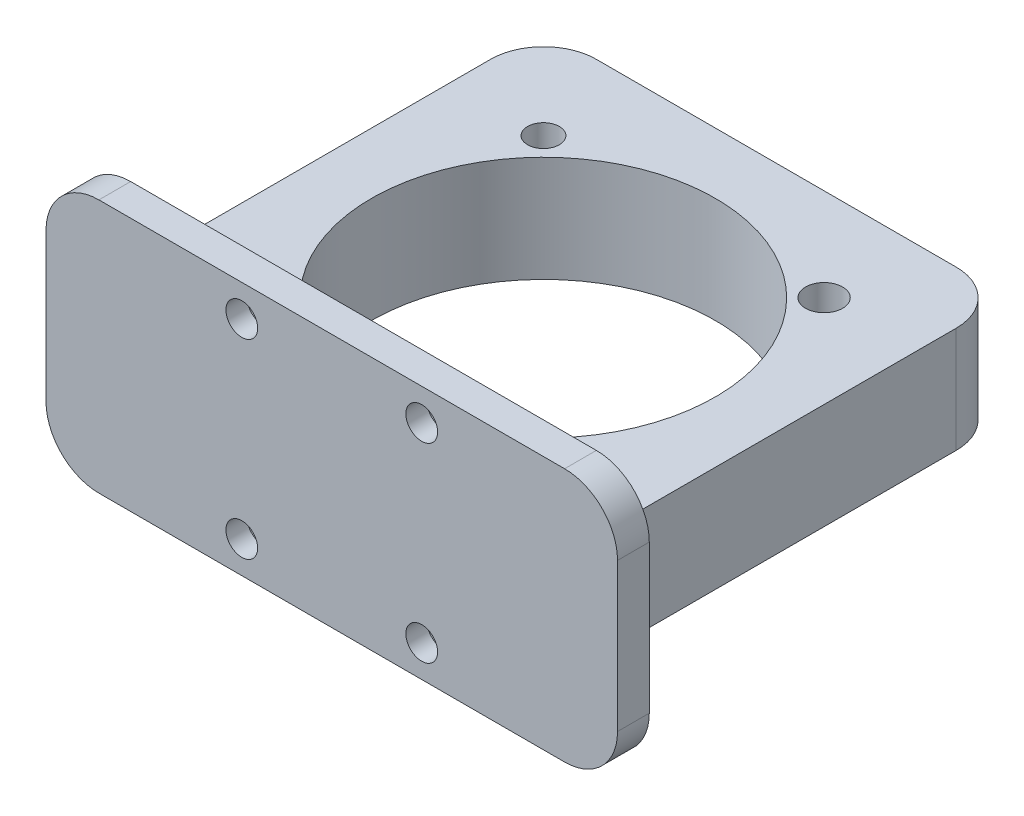
SolidWorks part; units mm, degrees
ref_plane "前视基准面" through (0, 0, 0) normal (0, 0, 1) x (1, 0, 0)
ref_plane "上视基准面" through (0, 0, 0) normal (0, 1, 0) x (1, 0, 0)
ref_plane "右视基准面" through (0, 0, 0) normal (1, 0, 0) x (0, 0, -1)
other "Configuration Table"
sketch "草图1" plane through (0, 0, 0) normal (0, 1, 0) x (1, 0, 0)
  line L1 (17, 17) -> (-17, 17)
  line L2 (17, 17) -> (17, -17)
  line L3 (17, -17) -> (-17, -17)
  line L4 (-17, 17) -> (-17, -17)
  line L5 (17, 17) -> (-17, -17) construction
  line L6 (17, -17) -> (-17, 17) construction
  circle A0 centre (0, 0) radius 16.25
  circle A1 centre (13.2583, 13.2583) radius 1.75
  circle A2 centre (13.2583, -13.2583) radius 1.5
  circle A3 centre (-13.2583, 13.2583) radius 1.5
  circle A4 centre (-13.2583, -13.2583) radius 1.75
  point P0 (0, 0)
  dimension "D3" = 32.5
  dimension "D8" = 3.5
  dimension "D9" = 3
  dimension "D10" = 3.5
  dimension "D11" = 3
  dimension "D1" = 34
  dimension "D2" = 34
  dimension "D4" = 18.75
  dimension "D5" = 18.75
  dimension "D6" = 18.75
  dimension "D7" = 18.75
extrude "凸台-拉伸1" add sketch "草图1" along normal mid plane 10
sketch "草图2" plane through (0, 0, 0) normal (0, 1, 0) x (1, 0, 0)
  line L1 (17, -17) -> (-17, -17)
  line L2 (17, -17) -> (17, -20)
  line L3 (17, -20) -> (-17, -20)
  line L4 (-17, -17) -> (-17, -20)
  dimension "D1" = 34
  dimension "D2" = 20
extrude "凸台-拉伸2" add sketch "草图2" along normal blind 12
sketch "草图5" plane through (0, 0, 0) normal (0, 0, 1) x (1, 0, 0)
  line L0 (0, 0) -> (0, -50000) construction
  line L1 (-17, 6) -> (49983, 6) construction
  line L2 (-17, 12) -> (-17, 0) construction
  line L3 (0, 9) -> (-50000, 9) construction
  circle A0 centre (-8.5, 9) radius 1.5
  circle A1 centre (8.5, 9) radius 1.5
  point P7 (-17, 6)
  dimension "D3" = 3
  dimension "D1" = 3
  dimension "D2" = 8.5
extrude "切除-拉伸4" cut sketch "草图5" along normal through all
sketch "草图6" plane through (-17, 0, 0) normal (-1, 0, 0) x (0, 0, 1)
  line L0 (17, 12) -> (17, 5) construction
  line L1 (17, 12) -> (20, 12)
  line L2 (17, 12) -> (17, 0)
  line L3 (17, 0) -> (20, 0)
  line L4 (20, 12) -> (20, 0)
  line L5 (17, 12) -> (20, 12) construction
sketch "草图16" plane through (0, 0, -17) normal (0, 0, -1) x (-1, 0, 0)
  line L0 (17, 12) -> (17, 0) construction
  line L1 (-17, 5) -> (17, 5)
  line L2 (-17, 5) -> (-17, -5)
  line L3 (-17, -5) -> (17, -5)
  line L4 (17, 5) -> (17, -5)
  line L5 (-17, -5) -> (17, -5) construction
extrude "凸台-拉伸4" add sketch "草图16" along normal blind 5
sketch "草图17" plane through (-17, 0, 0) normal (-1, 0, 0) x (0, 0, 1)
  line L1 (-22, 5) -> (17, 5)
  line L2 (-22, 5) -> (-22, 0)
  line L3 (-22, 0) -> (17, 0)
  line L4 (17, 5) -> (17, 0)
extrude "凸台-拉伸5" add sketch "草图17" along normal blind 5
mirror "镜向1" about plane through (0, 0, 0) normal (1, 0, 0) of "凸台-拉伸5"
sketch "草图20" plane through (0, 0, 0) normal (0, -1, 0) x (1, 0, 0)
  line L1 (-22, 17) -> (-17, 17)
  line L2 (-22, 17) -> (-22, -22)
  line L3 (-22, -22) -> (-17, -22)
  line L4 (-17, 17) -> (-17, -22)
extrude "凸台-拉伸6" add sketch "草图20" along normal mid plane 10
sketch "草图22" plane through (0, 0, 0) normal (0, -1, 0) x (1, 0, 0)
  line L1 (22, -22) -> (17, -22)
  line L2 (22, -22) -> (22, 17)
  line L3 (22, 17) -> (17, 17)
  line L4 (17, -22) -> (17, 17)
extrude "凸台-拉伸7" add sketch "草图22" along normal mid plane 10
sketch "草图25" plane through (0, 0, 0) normal (0, -1, 0) x (1, 0, 0)
  line L1 (-17, 20) -> (17, 20)
  line L2 (-17, 20) -> (-17, 17)
  line L3 (-17, 17) -> (17, 17)
  line L4 (17, 20) -> (17, 17)
extrude "凸台-拉伸8" add sketch "草图25" along normal mid plane 24
sketch "草图26" plane through (-17, 0, 0) normal (-1, 0, 0) x (0, 0, 1)
  line L0 (20, 12) -> (20, -12) construction
  line L1 (17, 12) -> (20, 12)
  line L2 (17, 12) -> (17, -12)
  line L3 (17, -12) -> (20, -12)
  line L4 (20, 12) -> (20, -12)
  line L5 (20, -12) -> (17, -12) construction
extrude "凸台-拉伸9" add sketch "草图26" along normal blind 10
mirror "镜向2" about plane through (0, 0, 0) normal (1, 0, 0) of "凸台-拉伸9"
fillet "圆角1" radius 5 2 edges at (-22, 0, -22) (22, 0, -22)
fillet "圆角2" radius 5 4 edges at (-27, 12, 18.5) (27, 12, 18.5) (27, -12, 18.5) (-27, -12, 18.5)
sketch "草图27" plane through (0, 0, 17) normal (0, 0, -1) x (-1, 0, 0)
  line L0 (0, 0) -> (0, -50000) construction
  line L1 (22, -12) -> (-22, -12) construction
  circle A0 centre (8.5, -9) radius 1.5
  circle A1 centre (8.5, -9) radius 2
  point P5 (0, -12)
  dimension "D3" = 3
  dimension "D4" = 4
  dimension "D1" = 8.5
  dimension "D2" = 3
extrude "切除-拉伸10" cut sketch "草图27" against normal through all contours A0
sketch "草图29" plane through (0, 0, 17) normal (0, 0, -1) x (-1, 0, 0)
  circle A0 centre (8.5, -9) radius 2
extrude "切除-拉伸11" cut sketch "草图29" against normal blind 1
mirror "镜向3" about plane through (0, 0, 0) normal (1, 0, 0) of "切除-拉伸10", "切除-拉伸11"
mirror "镜向4" about plane through (0, 0, 0) normal (0, 1, 0) of "镜向3", "切除-拉伸10", "切除-拉伸11"
sketch "草图15" plane through (0, 5, 0) normal (0, 1, 0) x (1, 0, 0)
